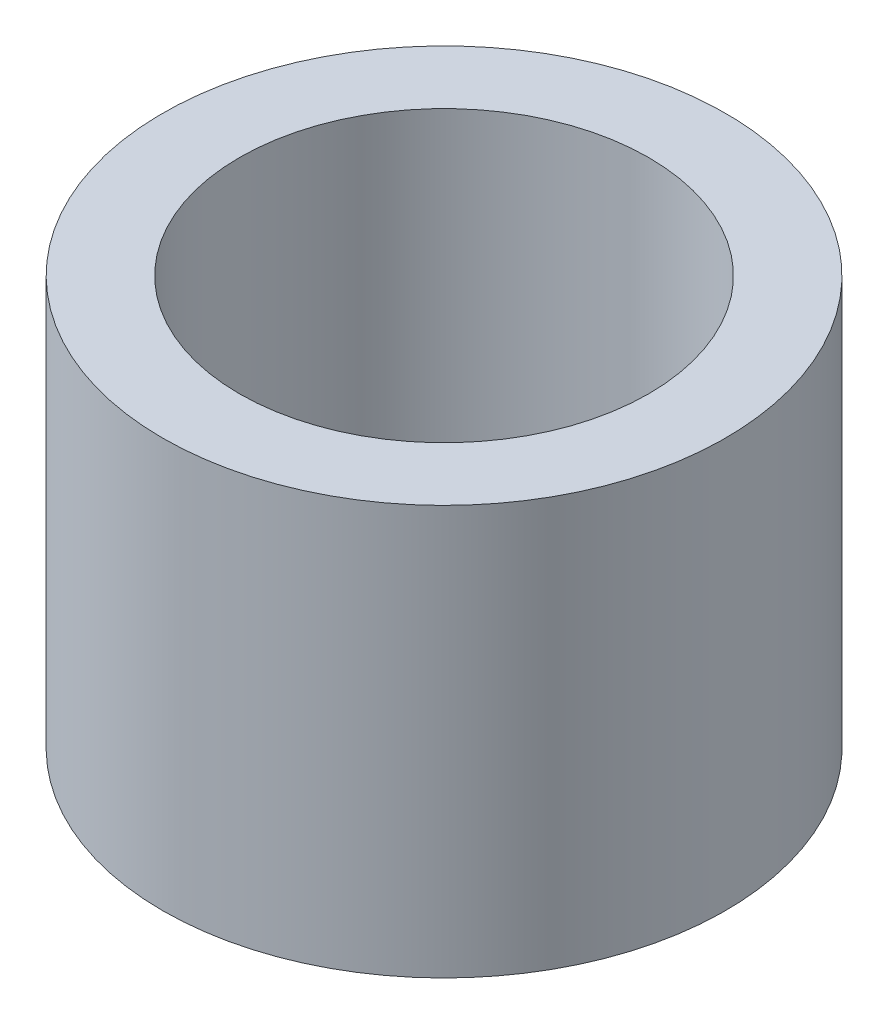
SolidWorks part; units mm, degrees
material "Leaded Commercial Bronze"
ref_plane "Front" through (0, 0, 0) normal (0, 0, 1) x (1, 0, 0)
ref_plane "Top" through (0, 0, 0) normal (0, 1, 0) x (1, 0, 0)
ref_plane "Right" through (0, 0, 0) normal (1, 0, 0) x (0, 0, -1)
sketch "Sketch1" plane through (0, 0, 0) normal (0, 1, 0) x (1, 0, 0)
  circle A0 centre (0, 0) radius 4
  circle A1 centre (0, 0) radius 5.5
  dimension "D1" = 8
  dimension "D2" = 11
extrude "Boss-Extrude1" add sketch "Sketch1" along normal blind 8
